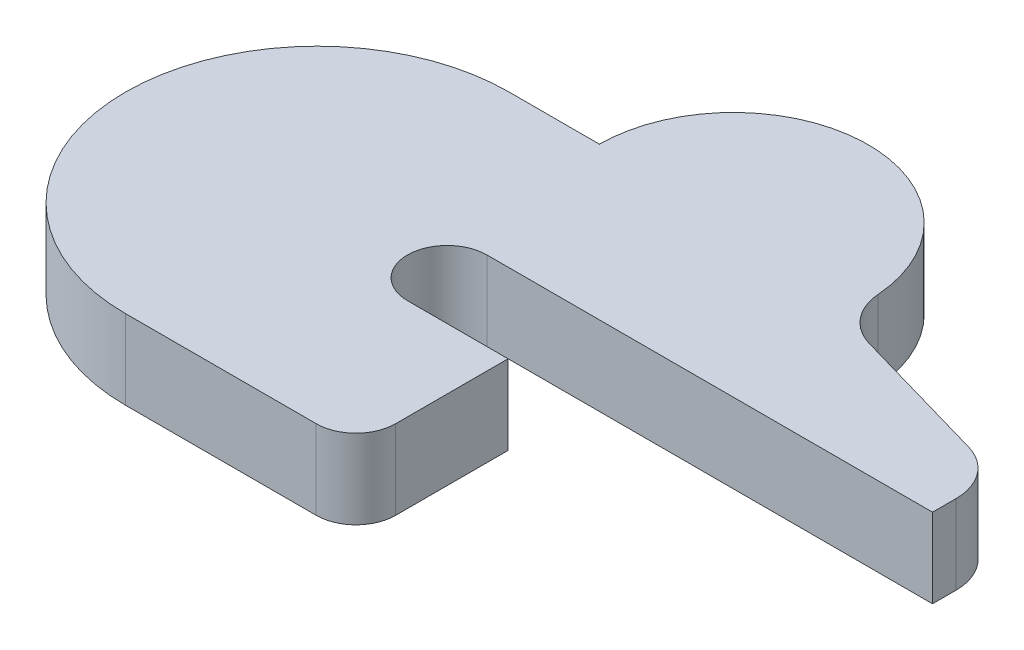
SolidWorks part; units mm, degrees
ref_plane "Front Plane" through (0, 0, 0) normal (0, 0, 1) x (1, 0, 0)
ref_plane "Top Plane" through (0, 0, 0) normal (0, 1, 0) x (1, 0, 0)
ref_plane "Right Plane" through (0, 0, 0) normal (1, 0, 0) x (0, 0, -1)
sketch "Sketch1" plane through (0, 0, 0) normal (0, 1, 0) x (1, 0, 0)
  line L0 (0, 0) -> (-3.8, 0)
  line L1 (-3.8, 3) -> (13.04, 3)
  line L2 (13.04, 3) -> (13.04, 3.8927)
  line L6 (-5.3, 8.7136) -> (-5.3, 8.75)
  line L7 (-5.3, 8.75) -> (-8.71, 8.75)
  line L9 (0, -4.25) -> (0, 0)
  line L10 (-8.71, -5.75) -> (-1.5, -5.75)
  line L11 (6.3287, 7.3242) -> (11.5913, 5.8152)
  arc A0 (-3.8, 0) -> (-3.8, 3) centre (-3.8, 1.5) cw
  arc A5 (-8.71, 8.75) -> (-8.71, -5.75) centre (-8.71, 1.5) ccw
  arc A10 (-1.5, -5.75) -> (0, -4.25) centre (-1.5, -4.25) ccw
  arc A11 (-5.3, 8.7136) -> (4.8856, 9.0966) centre (-0.2, 8.7136) cw
  arc A12 (4.8856, 9.0966) -> (6.3287, 7.3242) centre (6.88, 9.2468) ccw
  arc A13 (13.04, 3.8927) -> (11.5913, 5.8152) centre (11.04, 3.8927) ccw
  point P10 (-0.3916, 13.81)
  point P12 (-15.96, 1.5)
  point P15 (4.81, 7.7597)
  point P44 (-5.3, 1.5)
  dimension "10.9" = 7.25
  dimension "D4" = 1.5
  dimension "D5" = 19.56
  dimension "D6" = 16
  dimension "D7" = 2
  dimension "D11" = 1.5
  dimension "D2" = 5.1
  dimension "D3" = 2
  dimension "80" = 90
  dimension "D8" = 16.84
  dimension "D9" = 3.8
  dimension "5" = 8.23
  dimension "27.7" = 29
extrude "Boss-Extrude2" add sketch "Sketch1" along normal blind 3
